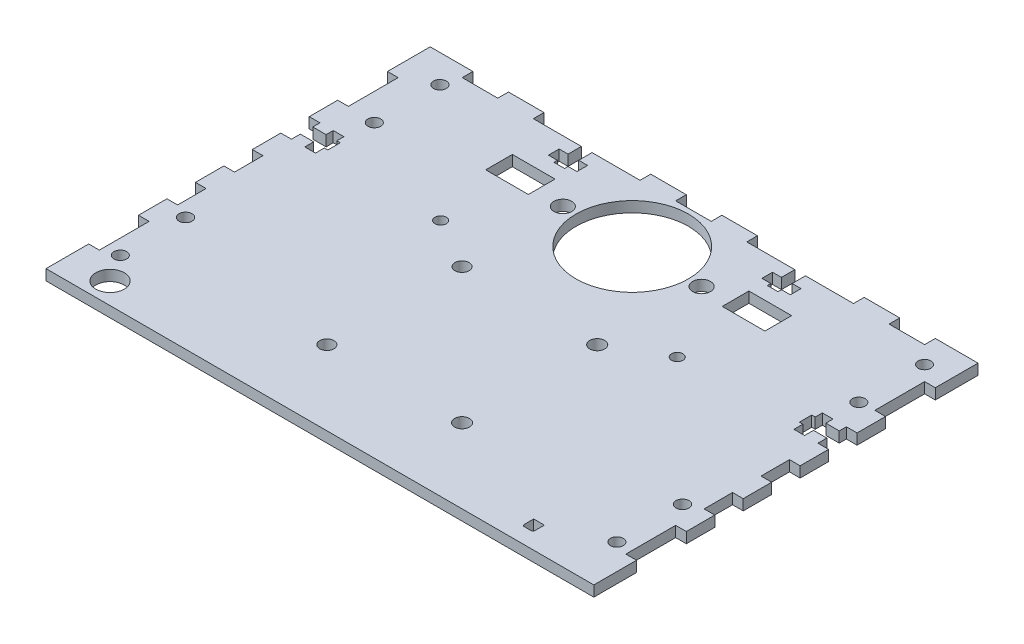
SolidWorks part; units mm, degrees
material "Balsa"
ref_plane "Alzado" through (0, 0, 0) normal (0, 0, 1) x (1, 0, 0)
ref_plane "Planta" through (0, 0, 0) normal (0, 1, 0) x (1, 0, 0)
ref_plane "Vista lateral" through (0, 0, 0) normal (1, 0, 0) x (0, 0, -1)
sketch "Croquis1" plane through (0, 0, 0) normal (0, 1, 0) x (1, 0, 0)
  line L0 (-77, 0) -> (-74, 0) construction
  line L1 (-77, -54) -> (77, -54)
  line L2 (-77, -54) -> (-77, 54)
  line L3 (-77, 54) -> (77, 54)
  line L4 (77, -54) -> (77, 54)
  line L5 (-77, -54) -> (77, 54) construction
  line L6 (-77, 54) -> (77, -54) construction
  line L7 (0, -54) -> (0, 54) construction
  line L8 (-74, 54) -> (-74, -54) construction
  line L9 (-77, -42) -> (-74, -42)
  line L10 (-77, 4) -> (-74, 4)
  line L11 (-77, 4) -> (-77, -4)
  line L12 (-77, -4) -> (-74, -4)
  line L13 (-74, 4) -> (-74, -4)
  line L14 (-77, 12) -> (-74, 12)
  line L15 (-77, 12) -> (-77, 20)
  line L16 (-77, 20) -> (-74, 20)
  line L17 (-74, 12) -> (-74, 20)
  line L22 (-77, 28) -> (-74, 28)
  line L23 (-77, 28) -> (-77, 42)
  line L24 (-77, 42) -> (-74, 42)
  line L25 (-74, 28) -> (-74, 42)
  line L26 (-74, -28) -> (-74, -42)
  line L27 (-77, -28) -> (-74, -28)
  line L28 (-77, -28) -> (-77, -42)
  line L29 (-77, -20) -> (-74, -20)
  line L30 (-74, -12) -> (-74, -20)
  line L31 (-77, -12) -> (-74, -12)
  line L32 (-77, -12) -> (-77, -20)
  line L33 (77, 42) -> (74, 42)
  line L34 (74, 28) -> (74, 42)
  line L35 (77, 28) -> (74, 28)
  line L36 (77, 28) -> (77, 42)
  line L37 (77, -28) -> (77, -42)
  line L38 (77, -28) -> (74, -28)
  line L39 (74, -28) -> (74, -42)
  line L40 (77, -42) -> (74, -42)
  line L41 (77, -12) -> (77, -20)
  line L42 (77, -12) -> (74, -12)
  line L43 (74, -12) -> (74, -20)
  line L44 (77, -20) -> (74, -20)
  line L45 (77, 20) -> (74, 20)
  line L46 (74, 12) -> (74, 20)
  line L47 (77, 12) -> (74, 12)
  line L48 (77, 12) -> (77, 20)
  line L49 (77, -4) -> (74, -4)
  line L50 (74, 4) -> (74, -4)
  line L51 (77, 4) -> (74, 4)
  line L52 (77, 4) -> (77, -4)
  line L53 (-77, 51) -> (77, 51) construction
  line L54 (-55, 51) -> (-65, 51)
  line L55 (-5, 54) -> (5, 54)
  line L56 (-5, 54) -> (-5, 51)
  line L57 (-5, 51) -> (5, 51)
  line L58 (5, 54) -> (5, 51)
  line L59 (15, 54) -> (45, 54)
  line L60 (15, 54) -> (15, 51)
  line L61 (15, 51) -> (45, 51)
  line L62 (45, 54) -> (45, 51)
  line L63 (55, 54) -> (65, 54)
  line L64 (55, 54) -> (55, 51)
  line L65 (55, 51) -> (65, 51)
  line L66 (65, 54) -> (65, 51)
  line L67 (-65, 54) -> (-65, 51)
  line L68 (-55, 54) -> (-65, 54)
  line L69 (-55, 54) -> (-55, 51)
  line L70 (-15, 51) -> (-45, 51)
  line L71 (-45, 54) -> (-45, 51)
  line L72 (-15, 54) -> (-45, 54)
  line L73 (-15, 54) -> (-15, 51)
  line L74 (-77, -48) -> (77, -48) construction
  line L75 (-30, 51) -> (-30, 10.4132) construction
  line L76 (53, -49.6) -> (55, -49.6)
  line L77 (52.5, -49.1) -> (52.5, -46.4)
  line L78 (52.5, -46.4) -> (55.5, -46.4)
  line L79 (55.5, -49.1) -> (55.5, -46.4)
  line L80 (52.5, -49.6) -> (55.5, -46.4) construction
  line L81 (52.5, -46.4) -> (55.5, -49.6) construction
  line L83 (-74, 1.5) -> (-74, -1.5)
  line L90 (-31.5, 51) -> (-28.5, 51)
  line L91 (-31.5, 51) -> (-31.5, 43.27)
  line L92 (-31.5, 43.27) -> (-28.5, 43.27)
  line L93 (-28.5, 51) -> (-28.5, 43.27)
  line L94 (-34, 47.25) -> (-26, 47.25)
  line L95 (-34, 47.25) -> (-34, 44.25)
  line L96 (-34, 44.25) -> (-26, 44.25)
  line L97 (-26, 47.25) -> (-26, 44.25)
  line L98 (31.5, 43.27) -> (28.5, 43.27)
  line L99 (28.5, 51) -> (28.5, 43.27)
  line L100 (31.5, 51) -> (28.5, 51)
  line L101 (31.5, 51) -> (31.5, 43.27)
  line L102 (34, 44.25) -> (26, 44.25)
  line L103 (26, 47.25) -> (26, 44.25)
  line L104 (34, 47.25) -> (26, 47.25)
  line L105 (34, 47.25) -> (34, 44.25)
  line L109 (74, 1.5) -> (74, -1.5)
  line L114 (-74, 16) -> (74, 16) construction
  line L115 (74, 17.9921) -> (66.27, 17.9921)
  line L116 (-74, 14.4979) -> (-66.27, 14.4979)
  line L117 (-74, 14.4979) -> (-74, 17.9921)
  line L118 (-74, 17.9921) -> (-66.27, 17.9921)
  line L119 (-66.27, 14.4979) -> (-66.27, 17.9921)
  line L120 (-70.25, 12) -> (-67.25, 12)
  line L121 (-70.25, 12) -> (-70.25, 20)
  line L122 (-70.25, 20) -> (-67.25, 20)
  line L123 (-67.25, 12) -> (-67.25, 20)
  line L124 (66.27, 14.4979) -> (66.27, 17.9921)
  line L125 (74, 0) -> (77, 0) construction
  line L126 (74, 14.4979) -> (66.27, 14.4979)
  line L127 (74, 14.4979) -> (74, 17.9921)
  line L128 (70.25, 20) -> (67.25, 20)
  line L129 (67.25, 12) -> (67.25, 20)
  line L130 (70.25, 12) -> (67.25, 12)
  line L131 (70.25, 12) -> (70.25, 20)
  circle A0 centre (-65, -48) radius 4
  arc A1 (55.5, -49.1) -> (55, -49.6) centre (55, -49.1) cw
  arc A2 (53, -49.6) -> (52.5, -49.1) centre (53, -49.1) cw
  point P0 (0, 0)
  point P78 (54, -48)
  point P123 (-75.5, 4)
  dimension "D17" = 8
  dimension "D22" = 0.5
  dimension "D1" = 108
  dimension "D2" = 154
  dimension "D3" = 3
  dimension "D4" = 4
  dimension "D5" = 3
  dimension "D6" = 8
  dimension "D7" = 8
  dimension "D8" = 8
  dimension "D9" = 14
  dimension "D10" = 3
  dimension "D11" = 5
  dimension "D12" = 10
  dimension "D13" = 10
  dimension "D14" = 30
  dimension "D15" = 10
  dimension "D16" = 10
  dimension "D18" = 6
  dimension "D19" = 23
  dimension "D20" = 3.2
  dimension "D21" = 3
  dimension "D23" = 12
  dimension "D31" = 3
  dimension "D32" = 8
  dimension "D33" = 1.5
  dimension "D34" = 4
  dimension "D35" = 0.98
  dimension "D36" = 7.73
  dimension "D37" = 8
  dimension "D38" = 7.73
  dimension "D39" = 3.4942
  dimension "D40" = 1.5021
  dimension "D41" = 0.98
  dimension "D42" = 8
  dimension "D43" = 4
  dimension "D44" = 3
extrude "Saliente-Extruir1" add sketch "Croquis1" along normal mid plane 2.9945
sketch "Croquis3" plane through (0, 1.4973, 0) normal (0, 1, 0) x (1, 0, 0)
  line L0 (-15, 54) -> (-5, 54) construction
  line L13 (5, 54) -> (15, 54) construction
  circle A0 centre (-19.5, 33.79) radius 2.5
  circle A1 centre (19.5, 33.79) radius 2.5
  dimension "D1" = 5
  dimension "D2" = 5
  dimension "D3" = 39
  dimension "D5" = 20.21
  dimension "D18" = 20.21
extrude "Cortar-Extruir2" cut sketch "Croquis3" against normal blind 3
sketch "Croquis4" plane through (0, -1.4973, 0) normal (0, -1, 0) x (1, 0, 0)
  circle A0 centre (0, -33.79) radius 15.8
  dimension "D1" = 31.6
extrude "Cortar-Extruir3" cut sketch "Croquis4" against normal blind 10
sketch "Croquis5" plane through (0, -1.4973, 0) normal (0, -1, 0) x (1, 0, 0)
  line L0 (0, 0) -> (0, -78.6163) construction
  line L1 (-39.25, -39.35) -> (-27.25, -39.35)
  line L2 (-39.25, -39.35) -> (-39.25, -31.85)
  line L3 (-39.25, -31.85) -> (-27.25, -31.85)
  line L4 (-27.25, -39.35) -> (-27.25, -31.85)
  line L5 (-39.25, -39.35) -> (-27.25, -31.85) construction
  line L6 (-39.25, -31.85) -> (-27.25, -39.35) construction
  line L7 (39.25, -31.85) -> (27.25, -39.35) construction
  line L8 (39.25, -39.35) -> (27.25, -31.85) construction
  line L9 (27.25, -39.35) -> (27.25, -31.85)
  line L10 (39.25, -31.85) -> (27.25, -31.85)
  line L11 (39.25, -39.35) -> (39.25, -31.85)
  line L12 (39.25, -39.35) -> (27.25, -39.35)
  point P0 (-33.25, -35.6)
  point P13 (33.25, -35.6)
  dimension "D1" = 7.5
  dimension "D2" = 12
extrude "Cortar-Extruir4" cut sketch "Croquis5" against normal blind 10
sketch "Croquis6" plane through (0, 1.4973, 0) normal (0, 1, 0) x (1, 0, 0)
  circle A0 centre (33.25, 13.2) radius 1.6
  circle A1 centre (-33.25, 13.2) radius 1.6
extrude "Cortar-Extruir5" cut sketch "Croquis6" against normal blind 10
sketch "Croquis9" plane through (0, 1.4973, 0) normal (0, 1, 0) x (1, 0, 0)
  line L0 (0, 0) -> (0, -26.1081) construction
  circle A0 centre (69.85, 46.1196) radius 1.7874
  circle A1 centre (69.8, 27.6931) radius 1.8
  circle A2 centre (69.85, -21.9257) radius 1.8327
  circle A3 centre (69.8, -40.3069) radius 1.8
  circle A4 centre (-69.8, -40.3069) radius 1.8
  circle A5 centre (-69.85, -21.9257) radius 1.8327
  circle A8 centre (-66.4, 27.6931) radius 1.8
  circle A9 centre (-66.4, 46.1196) radius 1.8124
extrude "Cortar-Extruir7" cut sketch "Croquis9" against normal blind 10
sketch "Croquis10" plane through (0, 1.4973, 0) normal (0, 1, 0) x (1, 0, 0)
  circle A0 centre (-19, 4.95) radius 2
  circle A1 centre (19, 4.95) radius 2.1
  circle A2 centre (19, -33.05) radius 2.1
  circle A3 centre (-19, -33.05) radius 2
extrude "Cortar-Extruir8" cut sketch "Croquis10" against normal blind 10
